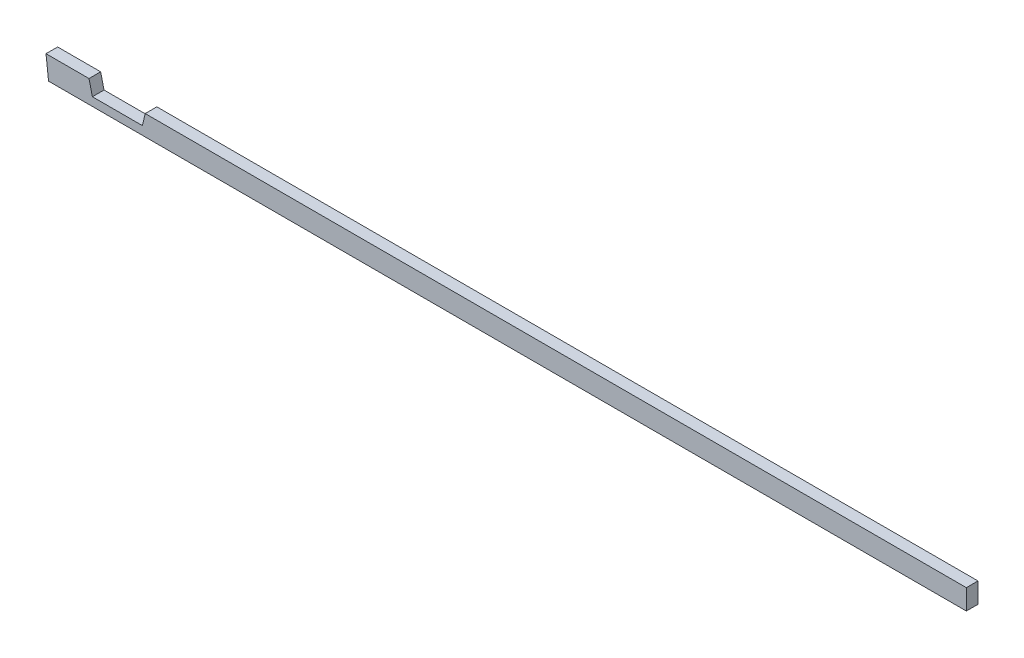
SolidWorks part; units mm, degrees
ref_plane "Front Plane" through (0, 0, 0) normal (0, 0, 1) x (1, 0, 0)
ref_plane "Top Plane" through (0, 0, 0) normal (0, 1, 0) x (1, 0, 0)
ref_plane "Right Plane" through (0, 0, 0) normal (1, 0, 0) x (0, 0, -1)
sketch "Sketch1" plane through (0, 0, 0) normal (0, 0, 1) x (1, 0, 0)
  line L0 (-742.8983, 1.0716) -> (-748.4403, 24.13)
  line L1 (-742.8983, 1.0716) -> (-661.0935, 1.0716)
  line L2 (-818.784, 24.13) -> (-814.5855, -12.7)
  line L3 (-814.5855, -12.7) -> (686.5686, -12.7)
  line L4 (686.5686, 20.4381) -> (686.5686, -12.7)
  line L5 (-748.4403, 24.13) -> (-818.784, 24.13)
  line L6 (-661.0935, 1.0716) -> (-656.5653, 20.4381)
  line L7 (-656.5653, 20.4381) -> (686.5686, 20.4381)
  point P0 (0, 0)
  dimension "D1" = 12.7
extrude "Boss-Extrude1" add sketch "Sketch1" along normal mid plane 19.05
